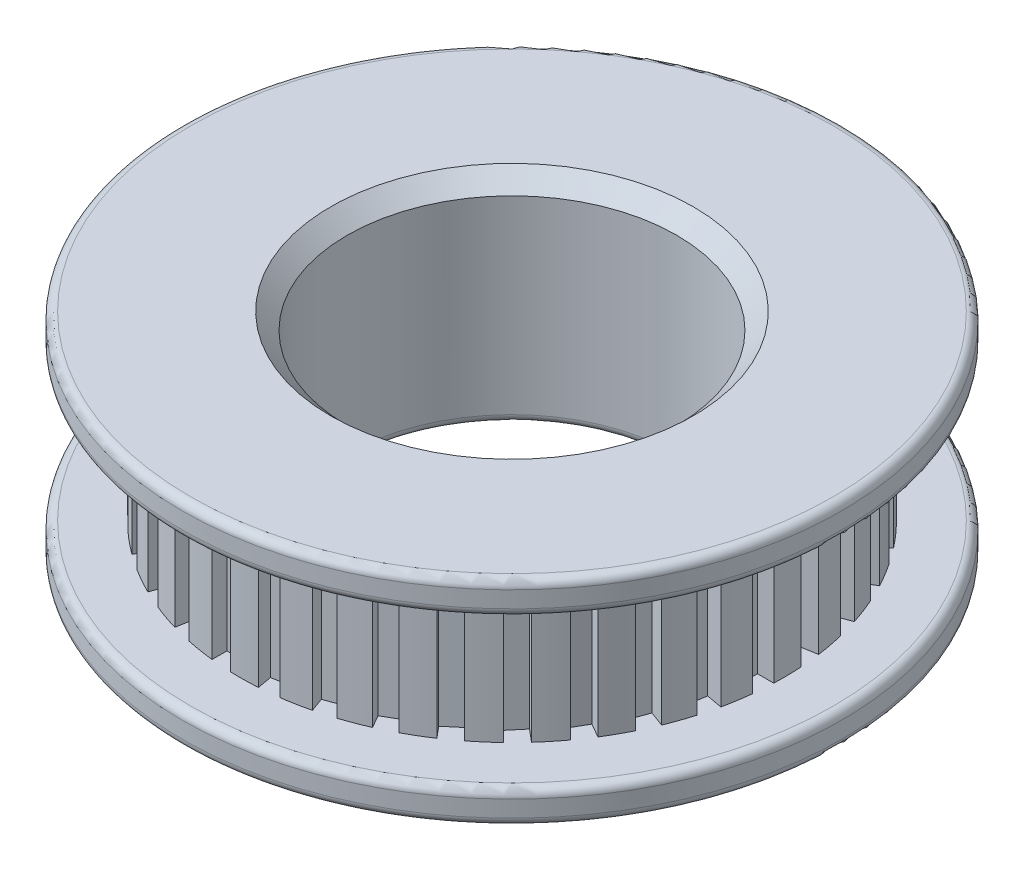
SolidWorks part; units mm, degrees
ref_plane "Front Plane" through (0, 0, 0) normal (0, 0, 1) x (1, 0, 0)
ref_plane "Top Plane" through (0, 0, 0) normal (0, 1, 0) x (1, 0, 0)
ref_plane "Right Plane" through (0, 0, 0) normal (1, 0, 0) x (0, 0, -1)
sketch "Sketch1" plane through (0, 0, 0) normal (0, 0, 1) x (1, 0, 0)
  line L0 (254, 0) -> (508, 0)
  line L1 (508, 0) -> (508, 50.8)
  line L2 (508, 50.8) -> (419.1, 50.8)
  line L3 (419.1, 50.8) -> (419.1, 279.4)
  line L4 (419.1, 279.4) -> (508, 279.4)
  line L5 (508, 279.4) -> (508, 330.2)
  line L6 (508, 330.2) -> (254, 330.2)
  line L7 (254, 330.2) -> (254, 0)
  line L8 (0, 0) -> (0, 345.2148) construction
  dimension "D1" = 254
  dimension "D2" = 254
  dimension "D3" = 254
  dimension "D4" = 50.8
  dimension "D5" = 50.8
  dimension "D6" = 330.2
  dimension "D7" = 88.9
revolve "Revolve1" add sketch "Sketch1" angle 360 about L8
chamfer "Chamfer1" distance 25.4 angle 45 1 edges at (0, 330.2, -254)
fillet "Fillet1" radius 12.7 4 edges at (0, 330.2, -508) (0, 279.4, -508) (0, 0, -508) (0, 50.8, -508)
sketch "Sketch3" plane through (0, 50.8, 0) normal (0, 1, 0) x (1, 0, 0)
  line L1 (15.24, 393.7) -> (45.72, 393.7)
  line L2 (15.24, 393.7) -> (15.24, 424.18)
  line L3 (15.24, 424.18) -> (45.72, 424.18)
  line L4 (45.72, 393.7) -> (45.72, 424.18)
  line L5 (15.24, 393.7) -> (45.72, 424.18) construction
  line L6 (15.24, 424.18) -> (45.72, 393.7) construction
  point P0 (30.48, 408.94)
  dimension "D1" = 30.48
  dimension "D2" = 30.48
  dimension "D3" = 393.7
  dimension "D4" = 15.24
extrude "Cut-Extrude1" cut sketch "Sketch3" along normal up to surface (228.6 mm away) up to face at (0, 279.4, -495.3)
pattern_circular "CirPattern1" count 36 every 10 about axis through (0, 0, 0) along (0, 1, 0) of "Cut-Extrude1"
fillet "Fillet2" radius 12.7 1 edges at (0, 0, -254)
